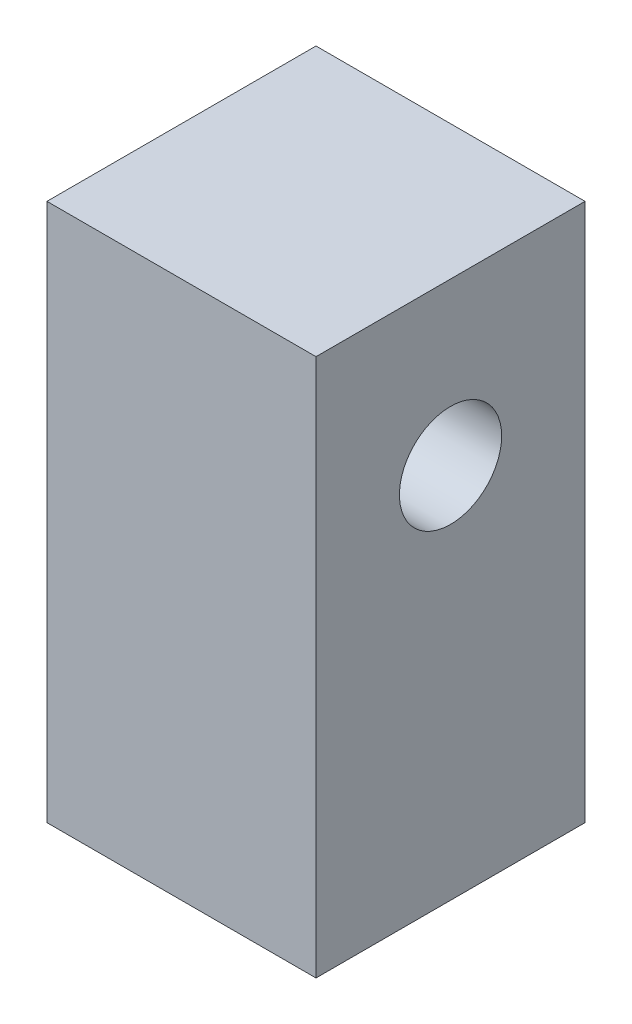
SolidWorks part; units mm, degrees
material "6061 Alloy"
ref_plane "Front Plane" through (0, 0, 0) normal (0, 0, 1) x (1, 0, 0)
ref_plane "Top Plane" through (0, 0, 0) normal (0, 1, 0) x (1, 0, 0)
ref_plane "Right Plane" through (0, 0, 0) normal (1, 0, 0) x (0, 0, -1)
sketch "Sketch1" plane through (0, 0, 0) normal (0, 1, 0) x (1, 0, 0)
  line L0 (-6.35, -6.35) -> (6.35, 6.35) construction
  line L1 (-6.35, 6.35) -> (6.35, 6.35)
  line L2 (-6.35, 6.35) -> (-6.35, -6.35)
  line L3 (-6.35, -6.35) -> (6.35, -6.35)
  line L4 (6.35, 6.35) -> (6.35, -6.35)
  dimension "D1" = 12.7
extrude "Boss-Extrude1" add sketch "Sketch1" along normal blind 25.4
sketch "Sketch2" plane through (6.35, 0, 0) normal (1, 0, 0) x (0, 0, -1)
  line L0 (0, 0) -> (0, 17.78) construction
  circle A0 centre (0, 17.78) radius 2.413
  dimension "D1" = 4.826
  dimension "D2" = 17.78
extrude "Cut-Extrude1" cut sketch "Sketch2" against normal through all
